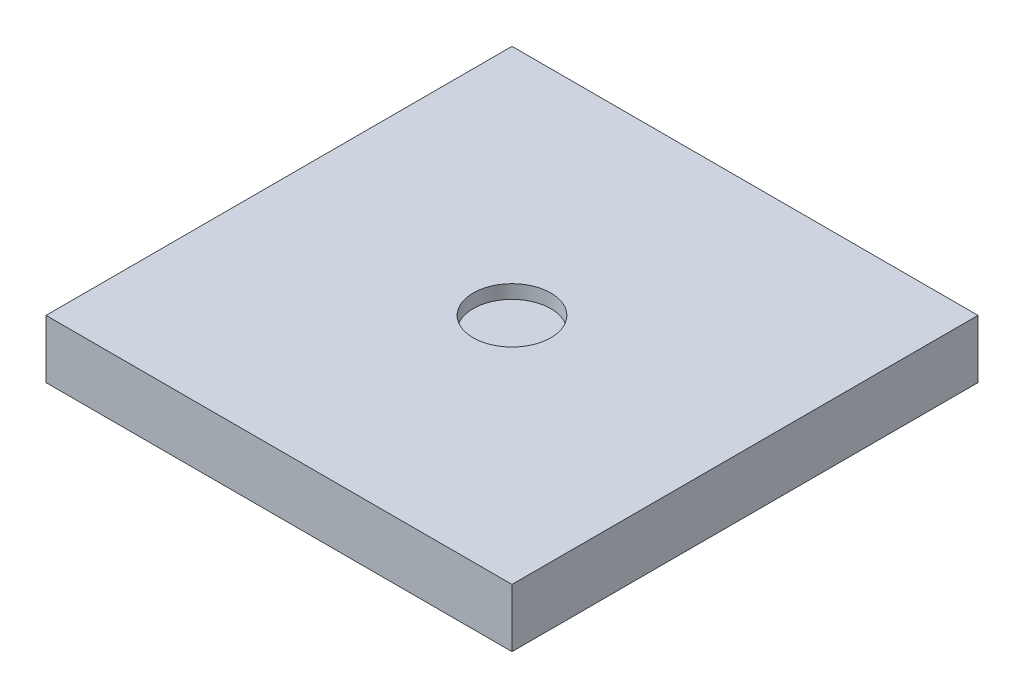
SolidWorks part; units mm, degrees
ref_plane "Front Plane" through (0, 0, 0) normal (0, 0, 1) x (1, 0, 0)
ref_plane "Top Plane" through (0, 0, 0) normal (0, 1, 0) x (1, 0, 0)
ref_plane "Right Plane" through (0, 0, 0) normal (1, 0, 0) x (0, 0, -1)
sketch "Sketch2" plane through (0, 0, 0) normal (0, 1, 0) x (1, 0, 0)
  line L1 (-76.2, 76.2) -> (76.2, 76.2)
  line L2 (-76.2, 76.2) -> (-76.2, -76.2)
  line L3 (-76.2, -76.2) -> (76.2, -76.2)
  line L4 (76.2, 76.2) -> (76.2, -76.2)
  line L5 (-76.2, 76.2) -> (76.2, -76.2) construction
  line L6 (-76.2, -76.2) -> (76.2, 76.2) construction
  point P0 (0, 0)
  dimension "D1" = 152.4
  dimension "D2" = 152.4
extrude "Boss-Extrude1" add sketch "Sketch2" along normal blind 19.05
sketch "Sketch3" plane through (0, 19.05, 0) normal (0, 1, 0) x (1, 0, 0)
  circle A0 centre (0, 0) radius 12.7
  dimension "D1" = 25.4
extrude "Cut-Extrude1" cut sketch "Sketch3" against normal blind 4.445
